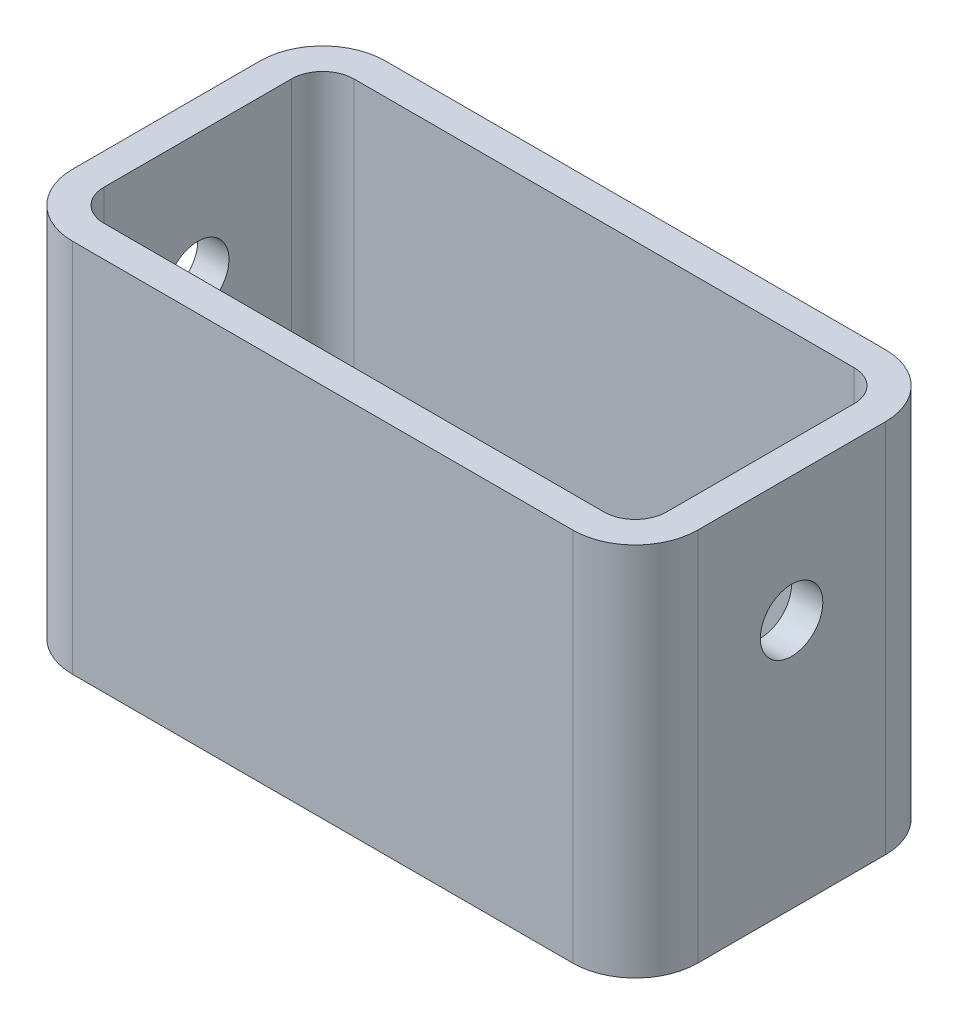
SolidWorks part; units mm, degrees
ref_plane "Front Plane" through (0, 0, 0) normal (0, 0, 1) x (1, 0, 0)
ref_plane "Top Plane" through (0, 0, 0) normal (0, 1, 0) x (1, 0, 0)
ref_plane "Right Plane" through (0, 0, 0) normal (1, 0, 0) x (0, 0, -1)
sketch "Sketch1" plane through (0, 0, 0) normal (0, 0, 1) x (1, 0, 0)
  line L1 (0, 0) -> (100, 0)
  line L2 (0, 0) -> (0, -60)
  line L3 (0, -60) -> (100, -60)
  line L4 (100, 0) -> (100, -60)
  dimension "D1" = 100
  dimension "D2" = 60
extrude "Boss-Extrude1" add sketch "Sketch1" along normal blind 50
fillet "Fillet1" radius 10 4 edges at (0, -30, 50) (0, -30, 0) (100, -30, 0) (100, -30, 50)
shell "Shell1" thickness 5
sketch "Sketch3" plane through (100, 0, 0) normal (1, 0, 0) x (0, 0, -1)
  line L0 (-40, -60) -> (-10, -60) construction
  line L3 (0, 0) -> (0, -60) construction
  circle A0 centre (-25, -20) radius 5
  point P4 (0, 0)
  point P6 (0, -20.1764)
  dimension "D1" = 10
  dimension "D2" = 40
  dimension "D3" = 25
extrude "Cut-Extrude1" cut sketch "Sketch3" against normal through all
